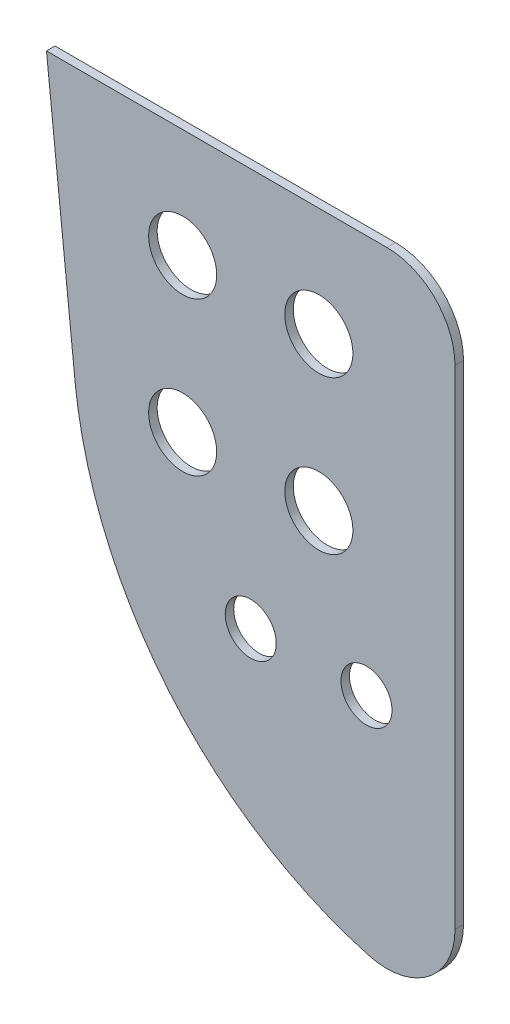
SolidWorks part; units mm, degrees
material "ASTM A36 Steel"
ref_plane "X-Y Datum" through (0, 0, 0) normal (0, 0, 1) x (1, 0, 0)
ref_plane "X-Z Datum" through (0, 0, 0) normal (0, 1, 0) x (1, 0, 0)
ref_plane "Y-Z Datum" through (0, 0, 0) normal (1, 0, 0) x (0, 0, -1)
sketch "Sketch1" plane through (0, 0, 0) normal (0, 0, 1) x (1, 0, 0)
  line L1 (96.1911, -185.6269) -> (-55.5753, -162.0679)
  line L10 (-132.424, 190.9765) -> (-145.9943, 61.7926)
  line L11 (-132.424, 190.9765) -> (-145.9943, 61.7926)
  line L12 (96.4882, 293.3455) -> (-57.5815, 269.5469)
  line L13 (272.8986, 235.8261) -> (143.226, 287.9689)
  line L14 (374.2191, 188.6716) -> (276.6913, 234.1801)
  line L15 (374.2197, -83.6631) -> (374.2191, 188.6716)
  line L16 (374.2197, -83.6631) -> (276.6921, -129.1718)
  line L17 (272.8993, -130.8178) -> (143.2519, -183.0234)
  line L18 (94.3963, -200.8018) -> (-55.5753, -177.5255)
  line L19 (-131.3776, -95.9269) -> (-145.9943, 43.2174)
  line L20 (-131.5113, -44.2164) -> (35.942, 52.505)
  line L21 (35.942, 52.505) -> (-132.8098, 149.9765)
  line L22 (-140.1048, -27.1737) -> (-2.8927, 52.505)
  line L23 (-2.8927, 52.505) -> (-142.3821, 133.5061)
  line L25 (-118.7223, -94.8368) -> (-133.3638, 44.5442)
  line L26 (-47.8398, -163.2687) -> (-47.8398, 4.1124)
  line L27 (-131.5113, -44.2164) -> (-47.8398, -44.2164)
  line L28 (96.3441, -188.2521) -> (-53.7043, -164.9638) construction
  arc A7 (-57.5815, 269.5469) -> (-132.424, 190.9765) centre (-44.0104, 181.6889) ccw
  arc A8 (143.226, 287.9689) -> (96.4882, 293.3455) centre (110.0593, 205.4875) ccw
  arc A9 (276.6913, 234.1801) -> (272.8986, 235.8261) centre (244.47, 165.1277) ccw
  arc A10 (272.8993, -130.8178) -> (276.6921, -129.1718) centre (244.4701, -60.1187) ccw
  arc A11 (94.3963, -200.8018) -> (143.2519, -183.0234) centre (89.5083, -111.3518) ccw
  arc A12 (-131.3776, -95.9269) -> (-55.5753, -177.5255) centre (-43.025, -89.8585) ccw
  arc A13 (-145.9943, 61.7926) -> (-145.9943, 43.2174) centre (-57.5808, 52.505) ccw
  arc A15 (-118.7223, -94.8368) -> (-53.7043, -164.9638) centre (-43.025, -89.8585) ccw construction
  ellipse E2 centre (-137.596, 141.7413) end of major axis (-133.6394, 148.5491) minor radius 4.7108
  ellipse E4 centre (-137.596, 141.7413) end of major axis (-132.8098, 149.9765) minor radius 5.6986
  ellipse E7 centre (-137.596, -36.7313) end of major axis (-141.5525, -29.9235) minor radius 4.7108
  ellipse E9 centre (-135.808, -35.6951) end of major axis (-140.1048, -27.1737) minor radius 5.6986
  spline S1 degree 3 poles (-55.5753, -162.0679) (-55.5938, -162.0651) (-55.6502, -162.0563) (-55.8584, -162.0236) (-56.3514, -161.9444) (-57.2982, -161.783) (-59.6017, -161.3512) (-62.6362, -160.6511) (-66.2582, -159.61) (-69.4664, -158.5284) (-72.6937, -157.2693) (-75.8603, -155.86) (-78.9595, -154.3036) (-81.9847, -152.6033) (-84.9295, -150.7629) (-87.7876, -148.7862) (-90.5529, -146.6776) (-93.2195, -144.4415) (-95.7819, -142.0828) (-98.2345, -139.6064) (-100.5722, -137.0176) (-102.79, -134.322) (-104.8833, -131.5254) (-106.8475, -128.6336) (-108.6786, -125.6529) (-110.3727, -122.5895) (-111.9262, -119.4501) (-113.3358, -116.2412) (-114.5986, -112.9697) (-115.7118, -109.6425) (-116.6732, -106.2668) (-117.4807, -102.8496) (-118.1326, -99.3982) (-118.49, -96.8861) (-118.6556, -95.4515) (-118.6898, -95.1411) (-118.7065, -94.9859) (-118.7159, -94.8974) (-118.7211, -94.8477) (-118.7223, -94.8368) knots 0 0 0 0 0.000571 0.001745 0.00644 0.015831 0.031092 0.078043 0.110904 0.146109 0.181308 0.216502 0.25169 0.286872 0.322047 0.357215 0.392376 0.42753 0.462676 0.497816 0.532948 0.568074 0.603192 0.638304 0.67341 0.708511 0.743605 0.778695 0.81378 0.84886 0.883937 0.919011 0.954083 0.989152 0.994997 0.997335 0.998503 0.999672 1 1 1 1
  point P47 (-124.0398, -44.2164)
  dimension "D2" = 76.2
  dimension "D1" = 12.7
extrude "Boss-Extrude1" add sketch "Sketch1" along normal blind 1.5875
sketch "Sketch2" plane through (0, 0, 0) normal (0, 0, -1) x (-1, 0, 0)
  line L1 (85.9398, -44.2164) -> (85.9398, -150.0539) construction
  line L2 (124.0398, -44.2164) -> (47.8398, -44.2164) construction
  line L3 (73.2398, -64.5364) -> (98.6398, -64.5364) construction
  line L4 (64.3498, -118.5114) -> (85.9398, -118.5114) construction
  circle A6 centre (98.6398, -93.1114) radius 6.35
  circle A7 centre (98.6398, -93.1114) radius 9.525
  circle A8 centre (98.6398, -64.5364) radius 6.35
  circle A9 centre (98.6398, -64.5364) radius 9.525
  circle A10 centre (73.2398, -93.1114) radius 6.35
  circle A11 centre (73.2398, -93.1114) radius 9.525
  circle A12 centre (73.2398, -64.5364) radius 6.35
  circle A13 centre (73.2398, -64.5364) radius 9.525
  circle A14 centre (85.9398, -118.5114) radius 4.7625
  circle A15 centre (64.3498, -118.5114) radius 4.7625
  circle A16 centre (85.9398, -118.5114) radius 7.9375
  circle A17 centre (64.3498, -118.5114) radius 7.9375
  spline S1 degree 3 poles (55.5753, -162.0679) (55.5938, -162.0651) (55.6502, -162.0563) (55.8584, -162.0236) (56.3514, -161.9444) (57.2982, -161.783) (59.6017, -161.3512) (62.6362, -160.6511) (66.2582, -159.61) (69.4664, -158.5284) (72.6937, -157.2693) (75.8603, -155.86) (78.9595, -154.3036) (81.9847, -152.6033) (84.9295, -150.7629) (87.7876, -148.7862) (90.5529, -146.6776) (93.2195, -144.4415) (95.7819, -142.0828) (98.2345, -139.6064) (100.5722, -137.0176) (102.79, -134.322) (104.8833, -131.5254) (106.8475, -128.6336) (108.6786, -125.6529) (110.3727, -122.5895) (111.9262, -119.4501) (113.3358, -116.2412) (114.5986, -112.9697) (115.7118, -109.6425) (116.6732, -106.2668) (117.4807, -102.8496) (118.1326, -99.3982) (118.49, -96.8861) (118.6556, -95.4515) (118.6898, -95.1411) (118.7065, -94.9859) (118.7159, -94.8974) (118.7211, -94.8477) (118.7223, -94.8368) knots 0 0 0 0 0.000571 0.001745 0.00644 0.015831 0.031092 0.078043 0.110904 0.146109 0.181308 0.216502 0.25169 0.286872 0.322047 0.357215 0.392376 0.42753 0.462676 0.497816 0.532948 0.568074 0.603192 0.638304 0.67341 0.708511 0.743605 0.778695 0.81378 0.84886 0.883937 0.919011 0.954083 0.989152 0.994997 0.997335 0.998503 0.999672 1 1 1 1 construction
  point P16 (85.9398, -64.5364)
  point P17 (75.1448, -118.5114)
  dimension "D1" = 12.7
  dimension "D2" = 19.05
  dimension "D3" = 9.525
  dimension "D4" = 15.875
  dimension "D9" = 21.59
  dimension "D5" = 25.4
  dimension "D6" = 20.32
  dimension "D7" = 28.575
  dimension "D8" = 25.4
extrude "Cut-Extrude1" cut sketch "Sketch2" against normal through all contours A15 | A14 | A10 | A6 | A8 | A12
fillet "Fillet1" radius 12.7 2 edges at (-47.8398, -44.2164, 0.7937) (-47.8398, -163.2687, 0.7937)
